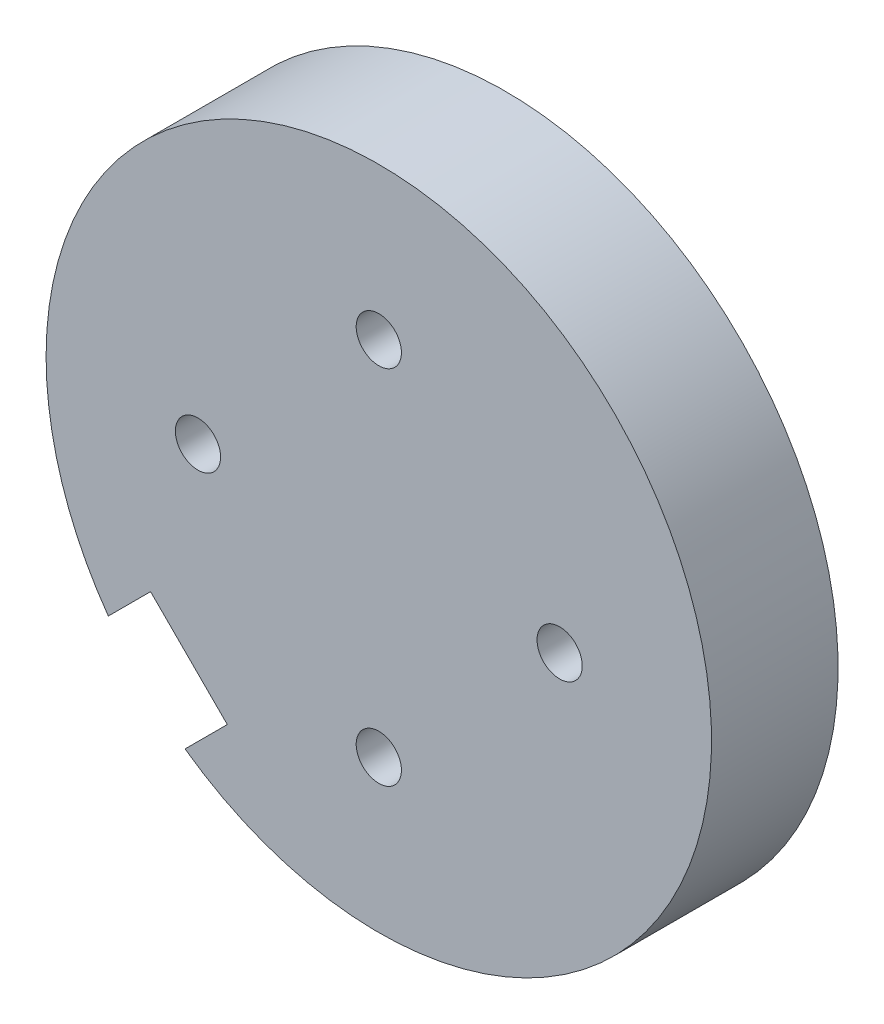
SolidWorks part; units mm, degrees
ref_plane "Alzado" through (0, 0, 0) normal (0, 0, 1) x (1, 0, 0)
ref_plane "Planta" through (0, 0, 0) normal (0, 1, 0) x (1, 0, 0)
ref_plane "Vista lateral" through (0, 0, 0) normal (1, 0, 0) x (0, 0, -1)
sketch "Croquis1" plane through (0, 0, 0) normal (0, 0, 1) x (1, 0, 0)
  circle A0 centre (0, 0) radius 18.4
  dimension "D1" = 36.8
extrude "Saliente-Extruir1" add sketch "Croquis1" along normal blind 26.3
sketch "Croquis2" plane through (0, 0, 26.3) normal (0, 0, 1) x (1, 0, 0)
  line L0 (0, -10) -> (-10, 0) construction
  line L4 (0, 0) -> (-13.0108, -13.0108) construction
  line L5 (-8.3792, -12.6218) -> (-12.6218, -8.3792)
  line L6 (-12.6218, -8.3792) -> (-14.958, -10.7153)
  line L7 (-8.3792, -12.6218) -> (-10.7153, -14.958)
  circle A1 centre (0, 0) radius 10 construction
  circle A2 centre (0, 10) radius 1.25
  circle A3 centre (10, 0) radius 1.25
  circle A4 centre (0, -10) radius 1.25
  circle A5 centre (-10, 0) radius 1.25
  circle A6 centre (0, 0) radius 18.4 construction
  arc A7 (-10.7153, -14.958) -> (-14.958, -10.7153) centre (0, 0) cw
  point P15 (0, 0)
  point P23 (-10.5005, -10.5005)
  dimension "D1" = 3
  dimension "D2" = 20
  dimension "D3" = 2.5
  dimension "D4" = 4
extrude "Cortar-Extruir1" cut sketch "Croquis2" against normal blind 5
sketch "Croquis3" plane through (0, 0, 0) normal (0, 0, -1) x (-1, 0, 0)
  circle A0 centre (0, 0) radius 10 construction
  circle A1 centre (-10, 0) radius 1.25
  circle A2 centre (0, 10) radius 1.25
  circle A3 centre (10, 0) radius 1.25
  circle A4 centre (0, -10) radius 1.25
  point P14 (0, 0)
  dimension "D1" = 20
  dimension "D2" = 2.5
  dimension "D3" = 4
extrude "Cortar-Extruir2" cut sketch "Croquis3" against normal blind 5
sketch "Croquis7" plane through (0, 0, 0) normal (0, 0, -1) x (-1, 0, 0)
  circle A0 centre (0, 0) radius 18.4
extrude "Cortar-Extruir5" cut sketch "Croquis7" against normal blind 19.3
sketch "Croquis8" plane through (0, 0, 19.3) normal (0, 0, -1) x (-1, 0, 0)
  circle A0 centre (0, 0) radius 6
extrude "Cortar-Extruir6" cut sketch "Croquis8" against normal blind 1
